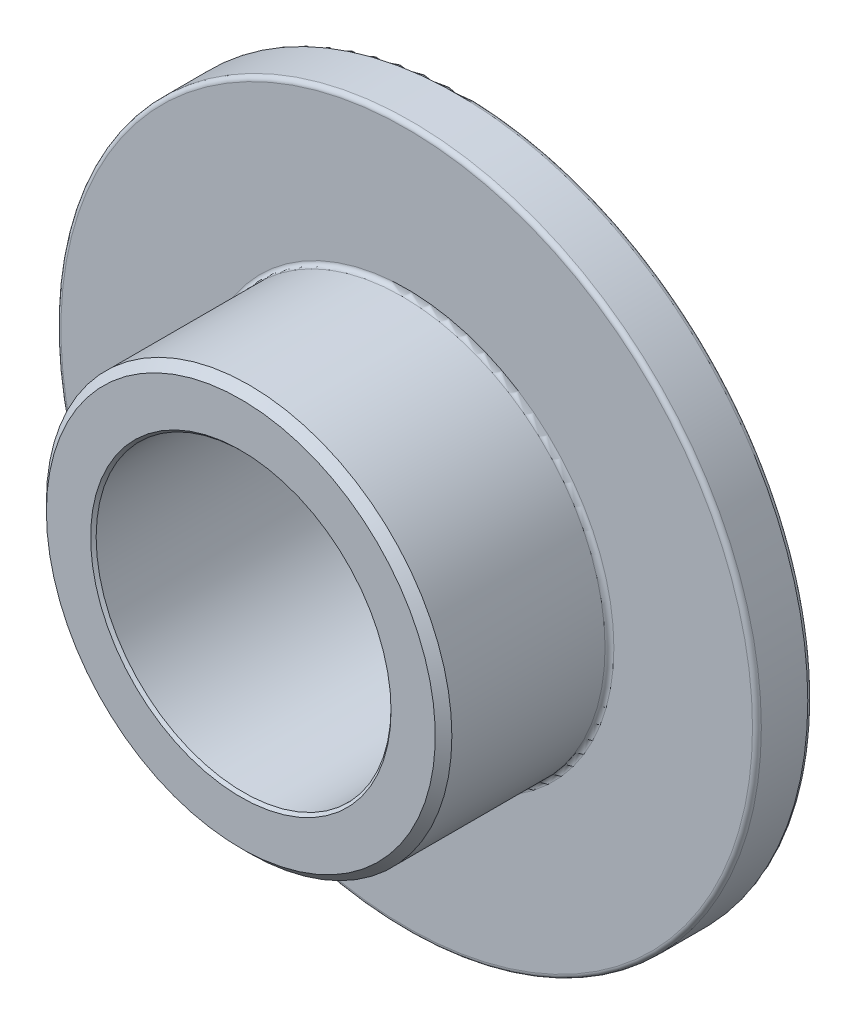
SolidWorks part; units mm, degrees
ref_plane "Front Plane" through (0, 0, 0) normal (0, 0, 1) x (1, 0, 0)
ref_plane "Top Plane" through (0, 0, 0) normal (0, 1, 0) x (1, 0, 0)
ref_plane "Right Plane" through (0, 0, 0) normal (1, 0, 0) x (0, 0, -1)
sketch "Sketch1" plane through (0, 0, 0) normal (0, 0, 1) x (1, 0, 0)
  circle A0 centre (0, 0) radius 2 construction
  circle A1 centre (0, 0) radius 2.75 construction
  circle A2 centre (0, 0) radius 4.75 construction
  point P5 (0, 4.75)
  dimension "ID" = 4
  dimension "OD" = 5.5
  dimension "Flange OD" = 9.5
sketch "Sketch2" plane through (0, 0, 0) normal (1, 0, 0) x (0, 0, -1)
  line L0 (-1.5, 0) -> (1.5, 0) construction
  line L1 (-1.5, 2.75) -> (-1.5, -2.75) construction
  line L2 (0, 2.75) -> (0, -2.75) construction
  line L3 (1.5, 4.75) -> (1.5, -4.75) construction
  line L4 (0, 4.75) -> (0, -4.75) construction
  line L5 (1.5, -4.75) -> (0.75, -4.75) construction
  dimension "Length" = 3
  dimension "Flange Thickness" = 0.75
sketch "Sketch3" plane through (0, 0, 0) normal (1, 0, 0) x (0, 0, -1)
  line L0 (1.5, -4.75) -> (0.75, -4.75)
  line L1 (0.75, -4.75) -> (0.75, -2.75)
  line L2 (0.75, -2.75) -> (-1.5, -2.75)
  line L3 (-1.5, -2.75) -> (-1.5, -2)
  line L4 (-1.5, 2.75) -> (-1.5, -2.75) construction
  line L5 (-1.5, -2) -> (1.5, -2)
  line L6 (1.5, 4.75) -> (1.5, -4.75) construction
  line L7 (1.5, -2) -> (1.5, -4.75)
  line L9 (0, 2) -> (0, -2) construction
  point P15 (0, -2)
revolve "Revolve1" add sketch "Sketch3" angle 360 about L0
chamfer "Chamfer1" distance 0.1125 angle 45 1 edges at (2.75, 0, 1.5)
chamfer "Chamfer2" distance 0.0375 angle 45 2 edges at (2, 0, -1.5) (2, 0, 1.5)
fillet "Fillet1" radius 0.06 3 edges at (4.75, 0, -1.5) (2.75, 0, -0.75) (4.75, 0, -0.75)
equation "\"D1@Chamfer1\"=(\"OD@Sketch1\"-\"ID@Sketch1\")*0.075"
equation "\"D1@Chamfer2\"=(\"OD@Sketch1\"-\"ID@Sketch1\")*0.025"
equation "\"D1@Fillet1\"=(\"Flange OD@Sketch1\"-\"OD@Sketch1\")*0.015"
